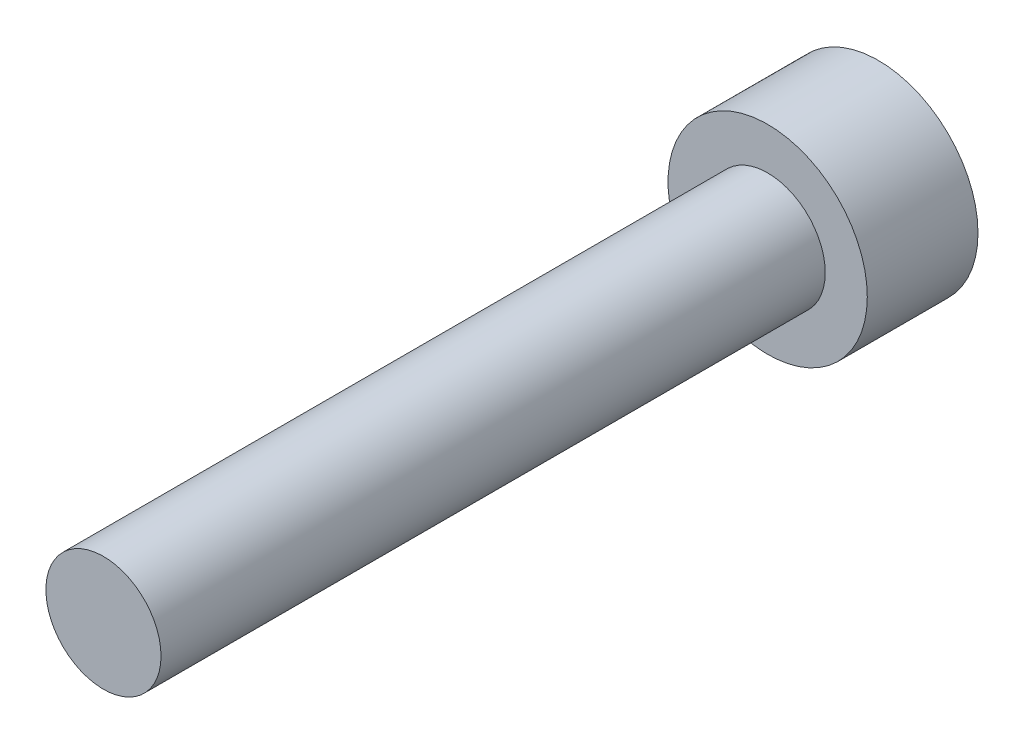
SolidWorks part; units mm, degrees
ref_plane "正面" through (0, 0, 0) normal (0, 0, 1) x (1, 0, 0)
ref_plane "平面" through (0, 0, 0) normal (0, 1, 0) x (1, 0, 0)
ref_plane "右側面" through (0, 0, 0) normal (1, 0, 0) x (0, 0, -1)
sketch "ｽｹｯﾁ1" plane through (0, 0, 0) normal (0, 0, 1) x (1, 0, 0)
  circle A0 centre (0, 0) radius 2.25
  dimension "D1" = 4.5
extrude "ﾎﾞｽ - 押し出し1" add sketch "ｽｹｯﾁ1" along normal blind 2.5
sketch "ｽｹｯﾁ2" plane through (0, 0, 2.5) normal (0, 0, 1) x (1, 0, 0)
  circle A0 centre (0, 0) radius 1.3
  dimension "D1" = 2.6
extrude "ﾎﾞｽ - 押し出し2" add sketch "ｽｹｯﾁ2" along normal blind 15
cosmetic thread "ねじ山1"
sketch "ｽｹｯﾁ3" plane through (0, 0, 0) normal (0, 0, -1) x (-1, 0, 0)
  line L1 (0.8522, -0.7637) -> (1.0875, 0.3562)
  line L2 (1.0875, 0.3562) -> (0.2352, 1.1199)
  line L3 (0.2352, 1.1199) -> (-0.8522, 0.7637)
  line L4 (-0.8522, 0.7637) -> (-1.0875, -0.3562)
  line L5 (-1.0875, -0.3562) -> (-0.2352, -1.1199)
  line L6 (-0.2352, -1.1199) -> (0.8522, -0.7637)
  circle A0 centre (0, 0) radius 0.991 construction
extrude "ｶｯﾄ - 押し出し1" cut sketch "ｽｹｯﾁ3" against normal blind 2
